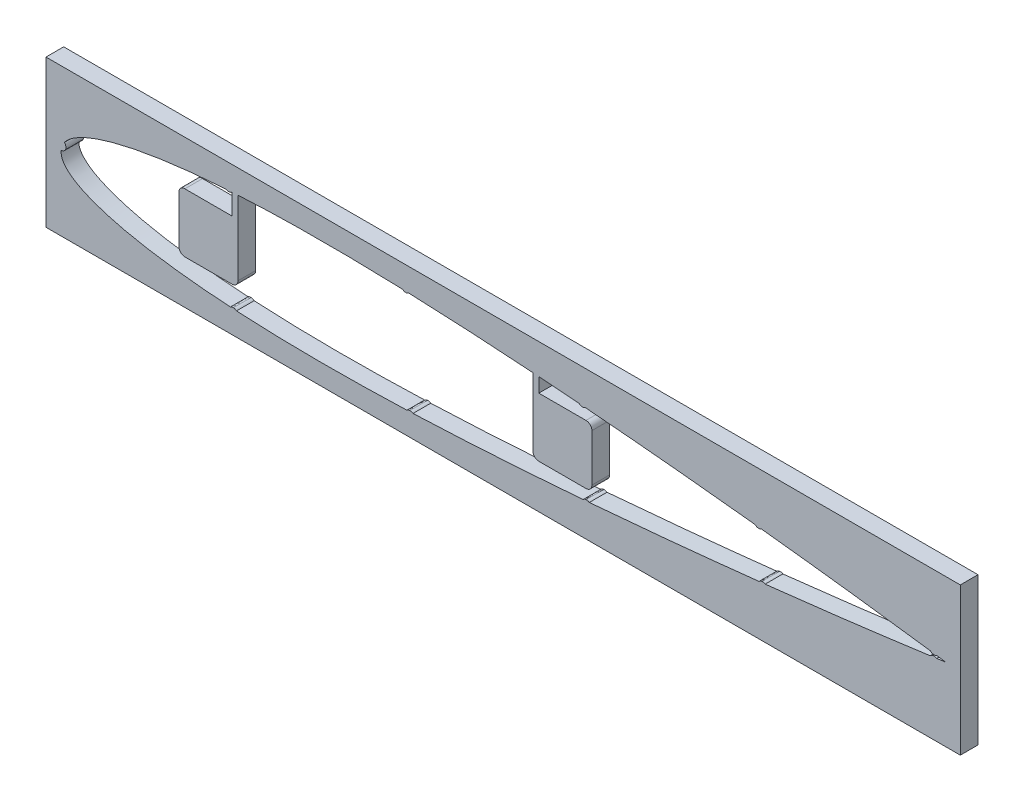
SolidWorks part; units mm, degrees
ref_plane "Front Plane" through (0, 0, 0) normal (0, 0, 1) x (1, 0, 0)
ref_plane "Top Plane" through (0, 0, 0) normal (0, 1, 0) x (1, 0, 0)
ref_plane "Right Plane" through (0, 0, 0) normal (1, 0, 0) x (0, 0, -1)
sketch "Sketch1" plane through (0, 0, 0) normal (0, 0, 1) x (1, 0, 0)
  line L0 (-120, 9.8744) -> (-120, 1.8744) construction
  line L1 (-121, 0.8744) -> (-129, 0.8744) construction
  line L2 (-130, 1.8744) -> (-130, 9.8744) construction
  line L3 (-129, 10.8744) -> (-121, 10.8744) construction
  line L4 (-69, 0.8744) -> (-61, 0.8744) construction
  line L5 (-60, 1.8744) -> (-60, 9.8744) construction
  line L6 (-61, 10.8744) -> (-69, 10.8744) construction
  line L7 (-70, 9.8744) -> (-70, 1.8744) construction
  line L8 (-120, 9.8744) -> (-120, 1.8744)
  line L9 (-121, 0.8744) -> (-129, 0.8744)
  line L10 (-130, 1.8744) -> (-130, 10.0267)
  line L11 (-129, 10.8744) -> (-121, 10.8744)
  line L12 (-69, 0.8744) -> (-61, 0.8744)
  line L13 (-60, 1.8744) -> (-60, 9.8744)
  line L14 (-61, 10.8744) -> (-69, 10.8744)
  line L15 (-70, 9.8744) -> (-70, 1.8744)
  line L17 (-152.5434, 18.4505) -> (2.4566, 18.4505)
  line L18 (-152.5434, 18.4505) -> (-152.5434, -6.5495)
  line L19 (-152.5434, -6.5495) -> (2.4566, -6.5495)
  line L20 (2.4566, 18.4505) -> (2.4566, -6.5495)
  line L23 (-130, 0.8744) -> (-130, 10.8744) construction
  line L25 (-120, 9.8744) -> (-120, 14.4423)
  line L26 (-121, 10.8744) -> (-121, 14.3833)
  line L27 (-70, 9.8744) -> (-70, 13.3822)
  line L28 (-69, 10.8744) -> (-69, 13.3102)
  arc A0 (-121, 0.8744) -> (-120, 1.8744) centre (-121, 1.8744) ccw construction
  arc A1 (-130, 1.8744) -> (-129, 0.8744) centre (-129, 1.8744) ccw construction
  arc A4 (-61, 0.8744) -> (-60, 1.8744) centre (-61, 1.8744) ccw construction
  arc A7 (-70, 1.8744) -> (-69, 0.8744) centre (-69, 1.8744) ccw construction
  arc A8 (-121, 0.8744) -> (-120, 1.8744) centre (-121, 1.8744) ccw
  arc A9 (-130, 1.8744) -> (-129, 0.8744) centre (-129, 1.8744) ccw
  arc A12 (-61, 0.8744) -> (-60, 1.8744) centre (-61, 1.8744) ccw
  arc A15 (-70, 1.8744) -> (-69, 0.8744) centre (-69, 1.8744) ccw
  arc A16 (-130, 10.0267) -> (-129, 10.8744) centre (-129.0762, 9.9505) cw
  arc A17 (-61, 10.8744) -> (-60, 9.8744) centre (-61, 9.8744) cw
  spline S0 degree 3 poles (-121.6767, 14.3405) (-123.1411, 14.2452) (-126.2973, 14.0029) (-130.9667, 13.5021) (-135.4976, 12.8298) (-138.9191, 12.1472) (-141.359, 11.5328) (-142.9668, 11.0631) (-144.4166, 10.5695) (-145.7052, 10.0535) (-146.8302, 9.5166) (-147.7896, 8.9602) (-148.5814, 8.3848) (-149.2065, 7.7898) (-149.6568, 7.1732) (-149.9459, 6.5323) (-149.9823, 6.09) (-150, 5.8744) knots 0.798611 0.798611 0.798611 0.798611 0.827398 0.860699 0.890714 0.917223 0.929108 0.94006 0.95007 0.959138 0.967274 0.9745 0.980863 0.986438 0.991348 0.995782 1 1 1 1
  spline S1 degree 3 poles (-70, 13.3822) (-74.6735, 13.7155) (-82.9004, 14.2269) (-94.5508, 14.6983) (-104.7314, 14.8688) (-113.1708, 14.7608) (-118.1884, 14.5447) (-120, 14.4423) knots 0.460414 0.460414 0.460414 0.460414 0.552321 0.622094 0.689119 0.752035 0.787628 0.787628 0.787628 0.787628
  spline S2 degree 3 poles (2000.7176, 12847.3131) (117.8045, -17.257) (58.8771, -2.4104) (-4.5792, 6.5192) (-13.4209, 7.7026) (-26.8721, 9.3357) (-41.2158, 10.89) (-55.5249, 12.2557) (-69.6159, 13.3992) (-82.7528, 14.2209) (-94.5508, 14.6983) (-104.7314, 14.8688) (-113.3466, 14.7586) (-120.3897, 14.4477) (-125.9153, 14.0438) (-130.9667, 13.5021) (-135.4976, 12.8298) (-138.9191, 12.1472) (-141.359, 11.5328) (-142.9668, 11.0631) (-144.4166, 10.5695) (-145.7052, 10.0535) (-146.8302, 9.5166) (-147.7896, 8.9602) (-148.5814, 8.3848) (-149.2065, 7.7898) (-149.6568, 7.1732) (-156.3437, -7.6511) (25.6528, -64.925) (-12832.7817, 2829.5198) knots -1.176109 -1.176109 -1.176109 -1.176109 0.000578 0.009225 0.080907 0.17556 0.275015 0.363913 0.457516 0.552321 0.622094 0.689119 0.752035 0.791076 0.827398 0.860699 0.890714 0.917223 0.929108 0.94006 0.95007 0.959138 0.967274 0.9745 0.980863 0.986438 0.991348 0.995782 1.300147 1.300147 1.300147 1.300147 only from (0, 5.8744) to (-150, 5.8744)
  spline S3 degree 3 poles (-4056.8979, -846.7209) (-70.4443, 44.7722) (-154.2663, 14.7942) (-149.6568, 4.5755) (-149.2065, 3.9589) (-148.5814, 3.3639) (-147.7896, 2.7885) (-146.8302, 2.2321) (-145.7052, 1.6952) (-144.4166, 1.1792) (-142.9668, 0.6856) (-141.359, 0.2159) (-138.9191, -0.3985) (-135.4976, -1.0811) (-130.9667, -1.7534) (-125.9153, -2.2951) (-120.3897, -2.699) (-113.3466, -3.0098) (-104.7314, -3.1201) (-94.5508, -2.9496) (-82.7528, -2.4722) (-69.6159, -1.6505) (-55.5249, -0.507) (-41.2158, 0.8587) (-26.8721, 2.4131) (-13.4209, 4.0462) (-4.5792, 5.2296) (39.581, 11.4438) (79.7046, 20.0987) (680.7442, -3934.1283) knots -0.202685 -0.202685 -0.202685 -0.202685 0.004218 0.008652 0.013562 0.019137 0.0255 0.032726 0.040862 0.04993 0.05994 0.070892 0.082777 0.109286 0.139301 0.172602 0.208924 0.247965 0.310881 0.377906 0.447679 0.542484 0.636087 0.724985 0.82444 0.919093 0.990775 0.999422 1.793868 1.793868 1.793868 1.793868 only from (-150, 5.8744) to (0, 5.8744)
  spline S4 degree 3 poles (0, 5.8744) (-0.0292, 5.8785) (-0.4948, 5.9444) (-4.5792, 6.5192) (-13.4209, 7.7026) (-26.8721, 9.3357) (-41.2158, 10.89) (-55.3393, 12.238) (-64.4267, 12.9781) (-69, 13.3102) knots 0 0 0 0 0.000578 0.009225 0.080907 0.17556 0.275015 0.363913 0.453858 0.453858 0.453858 0.453858
  spline S5 degree 3 poles (-150, 5.8744) (-149.9823, 5.6587) (-149.9459, 5.2164) (-149.6568, 4.5755) (-149.2065, 3.9589) (-148.5814, 3.3639) (-147.7896, 2.7885) (-146.8302, 2.2321) (-145.7052, 1.6952) (-144.4166, 1.1792) (-142.9668, 0.6856) (-141.359, 0.2159) (-138.9191, -0.3985) (-135.4976, -1.0811) (-130.9667, -1.7534) (-125.9153, -2.2951) (-120.3897, -2.699) (-113.3466, -3.0098) (-104.7314, -3.1201) (-94.5508, -2.9496) (-82.7528, -2.4722) (-69.6159, -1.6505) (-55.5249, -0.507) (-41.2158, 0.8587) (-26.8721, 2.4131) (-13.4209, 4.0462) (-4.5792, 5.2296) (-0.4948, 5.8043) (-0.0292, 5.8702) (0, 5.8744) knots 0 0 0 0 0.004218 0.008652 0.013562 0.019137 0.0255 0.032726 0.040862 0.04993 0.05994 0.070892 0.082777 0.109286 0.139301 0.172602 0.208924 0.247965 0.310881 0.377906 0.447679 0.542484 0.636087 0.724985 0.82444 0.919093 0.990775 0.999422 1 1 1 1
  spline S6 degree 3 poles (-121, 14.3833) (-121.2256, 14.3694) (-121.4511, 14.3552) (-121.6767, 14.3405) knots 0.794178 0.794178 0.794178 0.794178 0.798611 0.798611 0.798611 0.798611
  point P13 (-120.9436, 14.3868)
  point P14 (-121.6767, 14.3405)
  point P21 (-130, 5.9505)
  point P25 (-152.5434, 5.9505)
  dimension "D2" = 25
  dimension "D3" = 155
  dimension "D1" = 0
extrude "Boss-Extrude1" add sketch "Sketch1" along normal blind 3
sketch "Sketch3" plane through (0, 0, 3) normal (0, 0, 1) x (1, 0, 0)
  spline S2 degree 3 poles (680.7518, 3945.9266) (79.7049, -8.35) (39.5812, 0.3049) (-4.5792, 6.5192) (-13.4209, 7.7026) (-26.8721, 9.3357) (-41.2158, 10.89) (-55.5249, 12.2557) (-69.6159, 13.3992) (-82.7528, 14.2209) (-94.5508, 14.6983) (-104.7314, 14.8688) (-113.3466, 14.7586) (-120.3897, 14.4477) (-125.9153, 14.0438) (-130.9667, 13.5021) (-135.4976, 12.8298) (-138.9191, 12.1472) (-141.359, 11.5328) (-142.9668, 11.0631) (-144.4166, 10.5695) (-145.7052, 10.0535) (-146.8302, 9.5166) (-147.7896, 8.9602) (-148.5814, 8.3848) (-149.2065, 7.7898) (-149.6568, 7.1732) (-154.2664, -3.0458) (-70.4388, -33.0255) (-4057.2989, 858.5593) knots -0.793872 -0.793872 -0.793872 -0.793872 0.000578 0.009225 0.080907 0.17556 0.275015 0.363913 0.457516 0.552321 0.622094 0.689119 0.752035 0.791076 0.827398 0.860699 0.890714 0.917223 0.929108 0.94006 0.95007 0.959138 0.967274 0.9745 0.980863 0.986438 0.991348 0.995782 1.202692 1.202692 1.202692 1.202692 only from (0, 5.8744) to (-150, 5.8744)
  spline S3 degree 3 poles (-4056.8979, -846.7209) (-70.4443, 44.7722) (-154.2663, 14.7942) (-149.6568, 4.5755) (-149.2065, 3.9589) (-148.5814, 3.3639) (-147.7896, 2.7885) (-146.8302, 2.2321) (-145.7052, 1.6952) (-144.4166, 1.1792) (-142.9668, 0.6856) (-141.359, 0.2159) (-138.9191, -0.3985) (-135.4976, -1.0811) (-130.9667, -1.7534) (-125.9153, -2.2951) (-120.3897, -2.699) (-113.3466, -3.0098) (-104.7314, -3.1201) (-94.5508, -2.9496) (-82.7528, -2.4722) (-69.6159, -1.6505) (-55.5249, -0.507) (-41.2158, 0.8587) (-26.8721, 2.4131) (-13.4209, 4.0462) (-4.5792, 5.2296) (39.581, 11.4438) (79.7046, 20.0987) (680.7442, -3934.1283) knots -0.202685 -0.202685 -0.202685 -0.202685 0.004218 0.008652 0.013562 0.019137 0.0255 0.032726 0.040862 0.04993 0.05994 0.070892 0.082777 0.109286 0.139301 0.172602 0.208924 0.247965 0.310881 0.377906 0.447679 0.542484 0.636087 0.724985 0.82444 0.919093 0.990775 0.999422 1.793868 1.793868 1.793868 1.793868 only from (-150, 5.8744) to (0, 5.8744)
  spline S4 degree 3 poles (0, 5.8744) (-0.0292, 5.8785) (-0.4948, 5.9444) (-4.5792, 6.5192) (-13.4209, 7.7026) (-26.8721, 9.3357) (-41.2158, 10.89) (-55.5249, 12.2557) (-69.6159, 13.3992) (-82.7528, 14.2209) (-94.5508, 14.6983) (-104.7314, 14.8688) (-113.3466, 14.7586) (-120.3897, 14.4477) (-125.9153, 14.0438) (-130.9667, 13.5021) (-135.4976, 12.8298) (-138.9191, 12.1472) (-141.359, 11.5328) (-142.9668, 11.0631) (-144.4166, 10.5695) (-145.7052, 10.0535) (-146.8302, 9.5166) (-147.7896, 8.9602) (-148.5814, 8.3848) (-149.2065, 7.7898) (-149.6568, 7.1732) (-149.9459, 6.5323) (-149.9823, 6.09) (-150, 5.8744) knots 0 0 0 0 0.000578 0.009225 0.080907 0.17556 0.275015 0.363913 0.457516 0.552321 0.622094 0.689119 0.752035 0.791076 0.827398 0.860699 0.890714 0.917223 0.929108 0.94006 0.95007 0.959138 0.967274 0.9745 0.980863 0.986438 0.991348 0.995782 1 1 1 1 construction
  spline S5 degree 3 poles (-150, 5.8744) (-149.9823, 5.6587) (-149.9459, 5.2164) (-149.6568, 4.5755) (-149.2065, 3.9589) (-148.5814, 3.3639) (-147.7896, 2.7885) (-146.8302, 2.2321) (-145.7052, 1.6952) (-144.4166, 1.1792) (-142.9668, 0.6856) (-141.359, 0.2159) (-138.9191, -0.3985) (-135.4976, -1.0811) (-130.9667, -1.7534) (-125.9153, -2.2951) (-120.3897, -2.699) (-113.3466, -3.0098) (-104.7314, -3.1201) (-94.5508, -2.9496) (-82.7528, -2.4722) (-69.6159, -1.6505) (-55.5249, -0.507) (-41.2158, 0.8587) (-26.8721, 2.4131) (-13.4209, 4.0462) (-4.5792, 5.2296) (-0.4948, 5.8043) (-0.0292, 5.8702) (0, 5.8744) knots 0 0 0 0 0.004218 0.008652 0.013562 0.019137 0.0255 0.032726 0.040862 0.04993 0.05994 0.070892 0.082777 0.109286 0.139301 0.172602 0.208924 0.247965 0.310881 0.377906 0.447679 0.542484 0.636087 0.724985 0.82444 0.919093 0.990775 0.999422 1 1 1 1 construction
  text T0 "......" font "Century Gothic" height 10
  text T1 "..... " font "Century Gothic" height 10
  dimension "D1" = 0
extrude "Boss-Extrude2" add sketch "Sketch3" against normal blind 3
sketch "Sketch4" plane through (0, 0, 3) normal (0, 0, 1) x (1, 0, 0)
  line L0 (-8.8023, 16.1235) -> (-8.8023, 11.4811)
  line L1 (-8.8023, 11.4811) -> (-8.8023, 16.1235)
  line L2 (-8.8023, 16.1235) -> (-9.933, 14.9929)
  line L3 (-9.933, 14.9929) -> (-8.8023, 16.1235)
  line L4 (-8.8023, 16.1235) -> (-7.6717, 14.9929)
